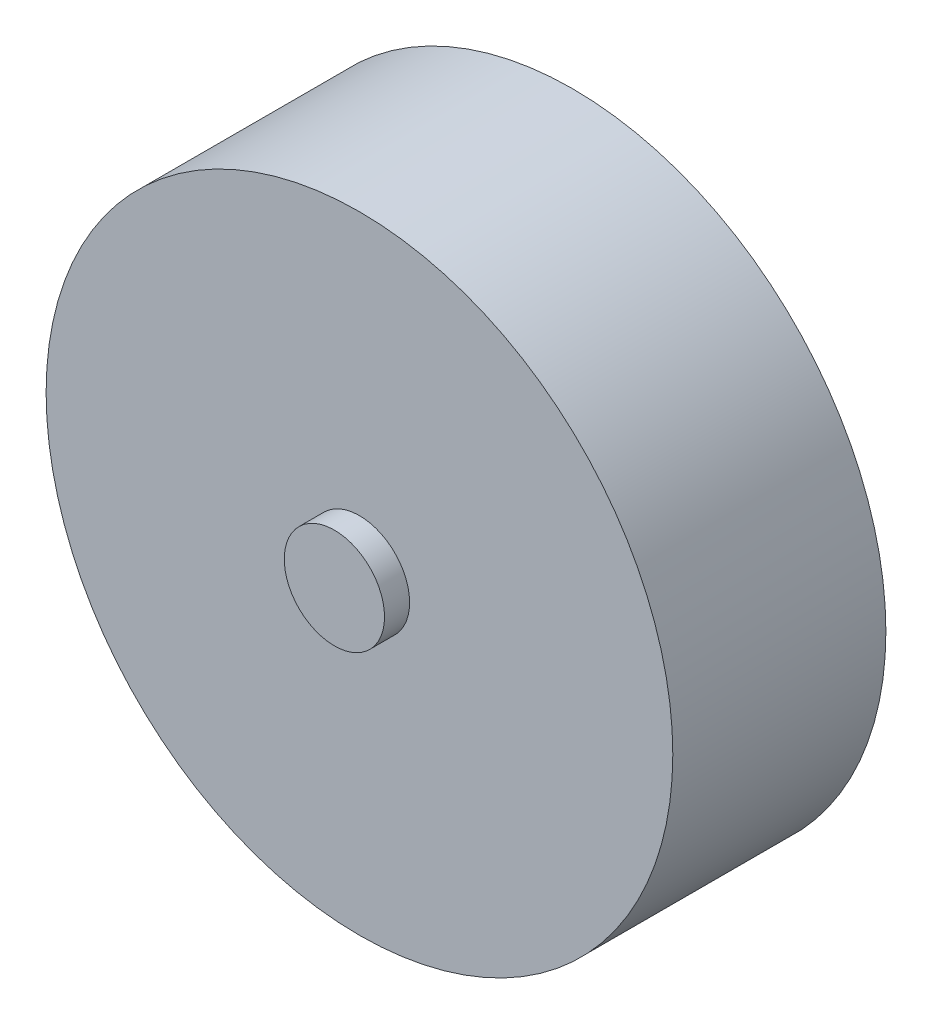
SolidWorks part; units mm, degrees
ref_plane "Front Plane" through (0, 0, 0) normal (0, 0, 1) x (1, 0, 0)
ref_plane "Top Plane" through (0, 0, 0) normal (0, 1, 0) x (1, 0, 0)
ref_plane "Right Plane" through (0, 0, 0) normal (1, 0, 0) x (0, 0, -1)
sketch "Sketch1" plane through (0, 0, 0) normal (0, 0, 1) x (1, 0, 0)
  circle A0 centre (0, 0) radius 250
  dimension "D1" = 500
extrude "Boss-Extrude1" add sketch "Sketch1" along normal blind 170
sketch "Sketch2" plane through (0, 0, 170) normal (0, 0, 1) x (1, 0, 0)
  circle A0 centre (0, 0) radius 40
  dimension "D1" = 80
extrude "Boss-Extrude2" add sketch "Sketch2" along normal blind 20 and the other way blind 190
